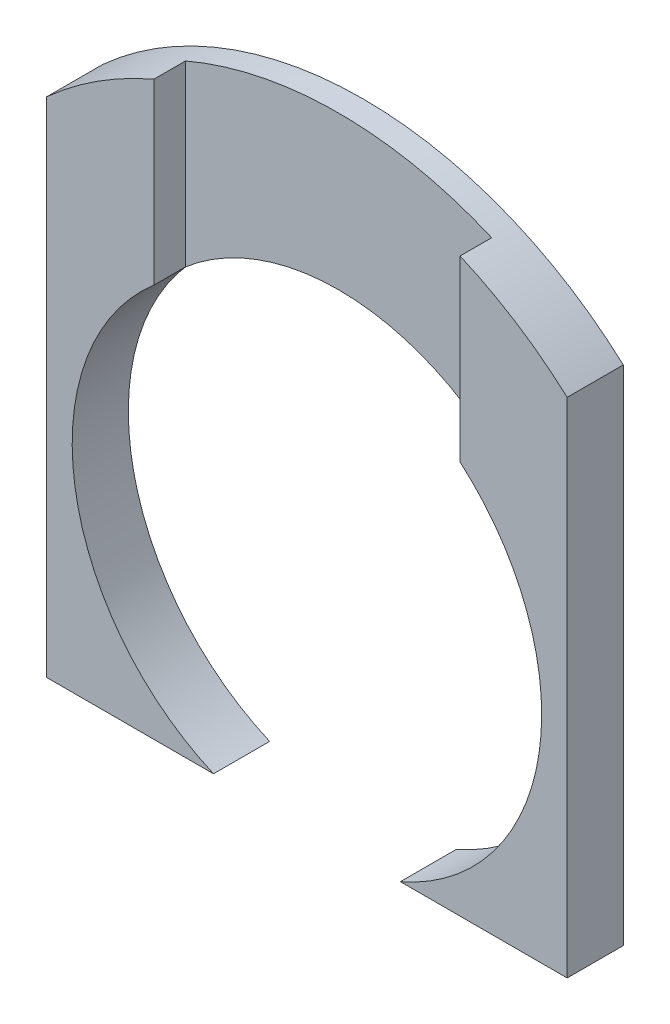
SolidWorks part; units mm, degrees
ref_plane "Front Plane" through (0, 0, 0) normal (0, 0, 1) x (1, 0, 0)
ref_plane "Top Plane" through (0, 0, 0) normal (0, 1, 0) x (1, 0, 0)
ref_plane "Right Plane" through (0, 0, 0) normal (1, 0, 0) x (0, 0, -1)
ref_plane "PZ_p30_100" through (0, 0, 30.1) normal (0, 0, 1) x (1, 0, 0)
sketch "S_cyl1" plane through (0, 0, 30.1) normal (0, 0, 1) x (1, 0, 0)
  circle A0 centre (0, 0) radius 19
  dimension "D1_S_cyl1" = 38
extrude "Boss_1" add sketch "S_cyl1" along normal blind 2.75
ref_plane "PZ_p30_000" through (0, 0, 30) normal (0, 0, 1) x (1, 0, 0)
sketch "S_hole2" plane through (0, 0, 30) normal (0, 0, 1) x (1, 0, 0)
  circle A0 centre (0, 0) radius 11.5
  dimension "D1_S_hole2" = 23
extrude "Hole_2" cut sketch "S_hole2" along normal blind 2.95
sketch "S_cut3" plane through (0, 0, 30) normal (0, 0, 1) x (1, 0, 0)
  line L0 (12.75, -20) -> (20, -20)
  line L1 (20, -20) -> (20, 20)
  line L2 (20, 20) -> (12.75, 20)
  line L3 (12.75, 20) -> (12.75, -20)
  dimension "P1" = 12.75
  dimension "P2" = 20
  dimension "P3" = 20
  dimension "P4" = 20
  dimension "P5" = 20
  dimension "P6" = 20
  dimension "P7" = 12.75
  dimension "P8" = 20
extrude "Pocket_3" cut sketch "S_cut3" along normal blind 2.95
sketch "S_cut4" plane through (0, 0, 30) normal (0, 0, 1) x (1, 0, 0)
  line L0 (-20, -20) -> (-12.75, -20)
  line L1 (-12.75, -20) -> (-12.75, 20)
  line L2 (-12.75, 20) -> (-20, 20)
  line L3 (-20, 20) -> (-20, -20)
  dimension "P1" = 20
  dimension "P2" = 20
  dimension "P3" = 12.75
  dimension "P4" = 20
  dimension "P5" = 12.75
  dimension "P6" = 20
  dimension "P7" = 20
  dimension "P8" = 20
extrude "Pocket_4" cut sketch "S_cut4" along normal blind 2.95
sketch "S_cut5" plane through (0, 0, 30) normal (0, 0, 1) x (1, 0, 0)
  line L0 (-20, -20) -> (20, -20)
  line L1 (20, -20) -> (20, -10.55)
  line L2 (20, -10.55) -> (-20, -10.55)
  line L3 (-20, -10.55) -> (-20, -20)
  dimension "P1" = 20
  dimension "P2" = 20
  dimension "P3" = 20
  dimension "P4" = 20
  dimension "P5" = 20
  dimension "P6" = 10.55
  dimension "P7" = 20
  dimension "P8" = 10.55
extrude "Pocket_5" cut sketch "S_cut5" along normal blind 2.95
ref_plane "PZ_p31_300" through (0, 0, 31.3) normal (0, 0, 1) x (1, 0, 0)
sketch "S_cut6" plane through (0, 0, 31.3) normal (0, 0, 1) x (1, 0, 0)
  line L0 (-7.5, 8.1) -> (7.5, 8.1)
  line L1 (7.5, 8.1) -> (7.5, 20)
  line L2 (7.5, 20) -> (-7.5, 20)
  line L3 (-7.5, 20) -> (-7.5, 8.1)
  dimension "P1" = 7.5
  dimension "P2" = 8.1
  dimension "P3" = 7.5
  dimension "P4" = 8.1
  dimension "P5" = 7.5
  dimension "P6" = 20
  dimension "P7" = 7.5
  dimension "P8" = 20
extrude "Pocket_6" cut sketch "S_cut6" along normal blind 1.65
equation "\"plate_t\" = 3"
equation "\"clearance\" = 0.5"
